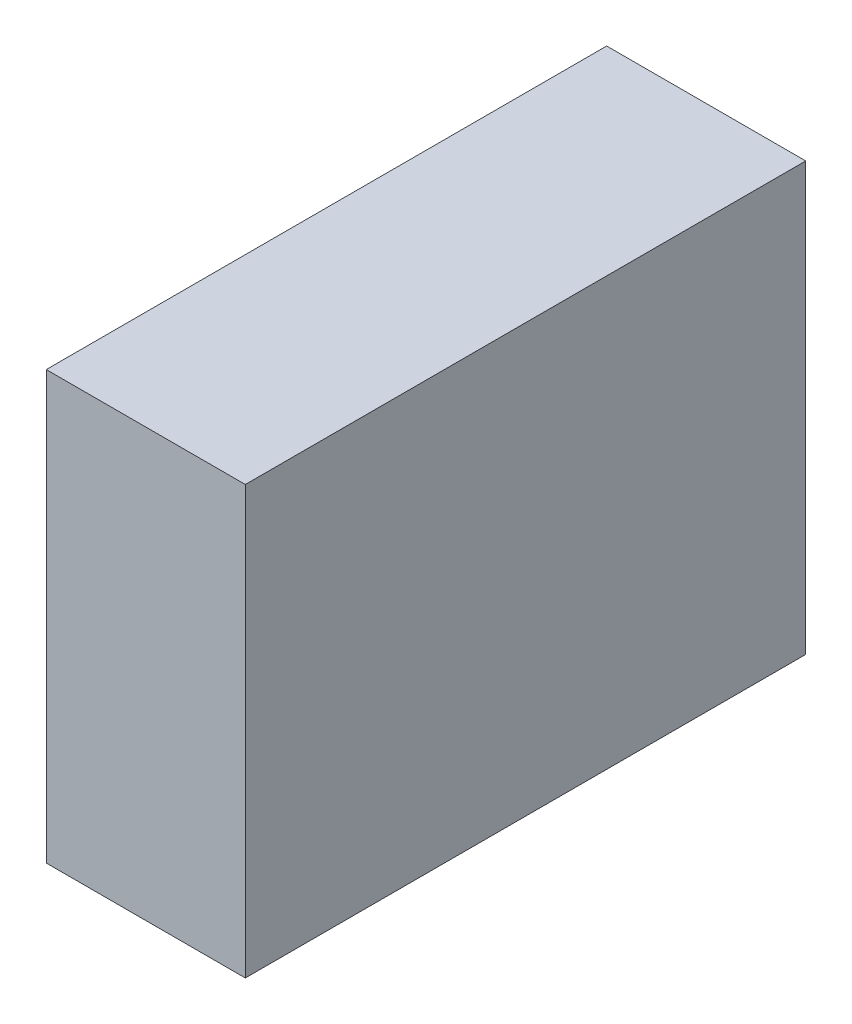
SolidWorks part; units mm, degrees
ref_plane "Front Plane" through (0, 0, 0) normal (0, 0, 1) x (1, 0, 0)
ref_plane "Top Plane" through (0, 0, 0) normal (0, 1, 0) x (1, 0, 0)
ref_plane "Right Plane" through (0, 0, 0) normal (1, 0, 0) x (0, 0, -1)
sketch "Sketch1" plane through (0, 0, 0) normal (0, 1, 0) x (1, 0, 0)
  line L1 (-26.797, -75.438) -> (26.797, -75.438)
  line L2 (-26.797, -75.438) -> (-26.797, 75.438)
  line L3 (-26.797, 75.438) -> (26.797, 75.438)
  line L4 (26.797, -75.438) -> (26.797, 75.438)
  line L5 (-26.797, -75.438) -> (26.797, 75.438) construction
  line L6 (-26.797, 75.438) -> (26.797, -75.438) construction
  point P0 (0, 0)
  dimension "D1" = 150.876
  dimension "D2" = 53.594
extrude "Boss-Extrude1" add sketch "Sketch1" along normal blind 115.062
hole_wizard "#6 Clearance Hole1" positions "Sketch3" profile "Sketch2" hole size "#6" standard "Ansi Inch"
sketch "Sketch3" plane through (0, 0, 0) normal (0, -1, 0) x (1, 0, 0)
  line L1 (-18.034, -69.977) -> (18.034, -69.977)
  line L2 (-18.034, -69.977) -> (-18.034, 69.977)
  line L3 (-18.034, 69.977) -> (18.034, 69.977)
  line L4 (18.034, -69.977) -> (18.034, 69.977)
  line L5 (-18.034, -69.977) -> (18.034, 69.977) construction
  line L6 (-18.034, 69.977) -> (18.034, -69.977) construction
  point P0 (18.034, 69.977)
  point P1 (-18.034, 69.977)
  point P3 (-18.034, -69.977)
  point P5 (18.034, -69.977)
  dimension "D1" = 36.068
  dimension "D2" = 139.954
sketch "Sketch2" plane through (18.034, 0, 69.977) normal (1, 0, 0) x (0, 0, -1)
  line L0 (0, 0) -> (0, 10.4374)
  line L1 (0, 10.4374) -> (2.1526, 9.144)
  line L2 (2.1526, 9.144) -> (2.1526, 0)
  line L5 (2.1526, 0) -> (0, 0)
  line L10 (0, 10.4374) -> (-2.1527, 9.144) construction
  line L11 (0, -6.35) -> (0, 107.95) construction
  dimension "Hole Dia." = 4.3053
  dimension "Hole Depth" = 9.144
  dimension "Drill Angle" = 118
